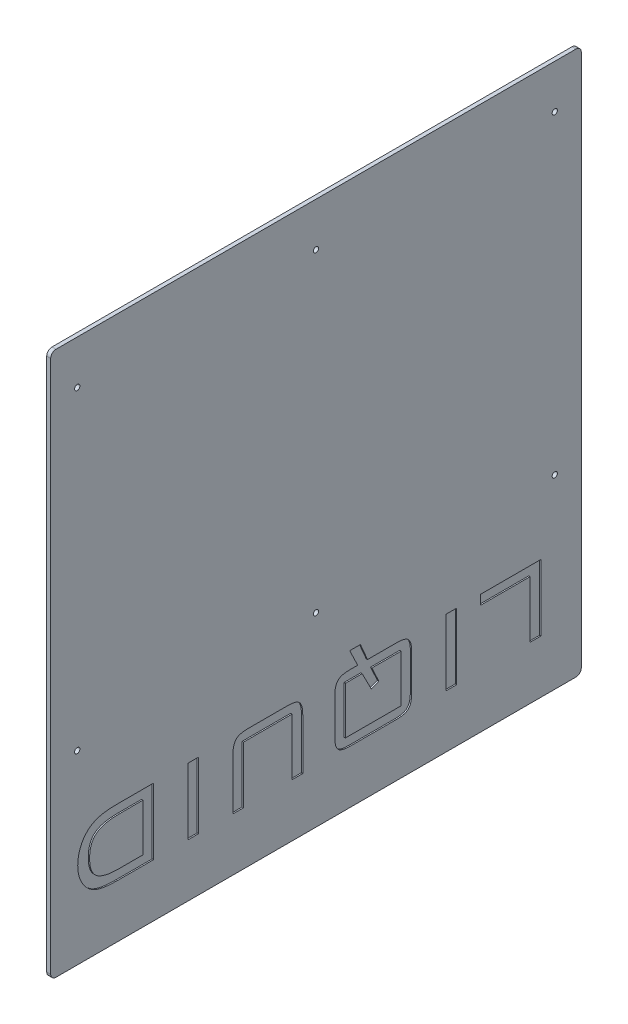
SolidWorks part; units mm, degrees
ref_plane "Front Plane" through (0, 0, 0) normal (0, 0, 1) x (1, 0, 0)
ref_plane "Top Plane" through (0, 0, 0) normal (0, 1, 0) x (1, 0, 0)
ref_plane "Right Plane" through (0, 0, 0) normal (1, 0, 0) x (0, 0, -1)
ref_plane "Plane1" through (322.6235, 0, 0) normal (1, 0, 0) x (0, 0, -1)
sketch "Sketch1" plane through (322.6235, 0, 0) normal (1, 0, 0) x (0, 0, -1)
  line L0 (-756.6779, 13.8398) -> (-364.6779, 13.8398)
  line L1 (-360.6779, 17.8398) -> (-360.6779, 419.8398)
  line L2 (-364.6779, 423.8398) -> (-756.6779, 423.8398)
  line L3 (-760.6779, 419.8398) -> (-760.6779, 17.8398)
  circle A0 centre (-740.6779, 153.8398) radius 2
  circle A1 centre (-740.6779, 390.8394) radius 2
  arc A2 (-760.6779, 17.8398) -> (-756.6779, 13.8398) centre (-756.6779, 17.8398) ccw
  arc A3 (-364.6779, 13.8398) -> (-360.6779, 17.8398) centre (-364.6779, 17.8398) ccw
  arc A4 (-360.6779, 419.8398) -> (-364.6779, 423.8398) centre (-364.6779, 419.8398) ccw
  arc A5 (-756.6779, 423.8398) -> (-760.6779, 419.8398) centre (-756.6779, 419.8398) ccw
  circle A6 centre (-380.6779, 153.8398) radius 2
  circle A7 centre (-380.6779, 390.8394) radius 2
  circle A8 centre (-560.6779, 390.8394) radius 2
  circle A9 centre (-560.6779, 153.8398) radius 2
  dimension "D1" = 4
  dimension "D6" = 33.0004
  dimension "D7" = 270
  dimension "D8" = 270
  dimension "D10" = 20
  dimension "D11" = 180
  dimension "D18" = 4
  dimension "D19" = 4
  dimension "D20" = 4
  dimension "D2" = 400
  dimension "D3" = 410
  dimension "D4" = 33.0004
  dimension "D5" = 33.0004
  dimension "D9" = 270
  dimension "D12" = 180
  dimension "D13" = 180
  dimension "D14" = 180
  dimension "D15" = 20
  dimension "D16" = 13.8398
  dimension "D17" = 360.6779
extrude "Boss-Extrude1" add sketch "Sketch1" against normal blind 3
sketch "Sketch3" plane through (322.6235, 0, 0) normal (-1, 0, 0) x (0, 0, 1)
  line L0 (378.6779, 103.8398) -> (716.8942, 103.8398) construction
  line L3 (360.6779, 17.8398) -> (360.6779, 419.8398) construction
  line L4 (756.6779, 13.8398) -> (364.6779, 13.8398) construction
  text T0 "LIQUID" font "BankGothic Lt BT" height 50
  dimension "D1" = 18
  dimension "D2" = 90
extrude "Cut-Extrude1" cut sketch "Sketch3" along normal blind 1
